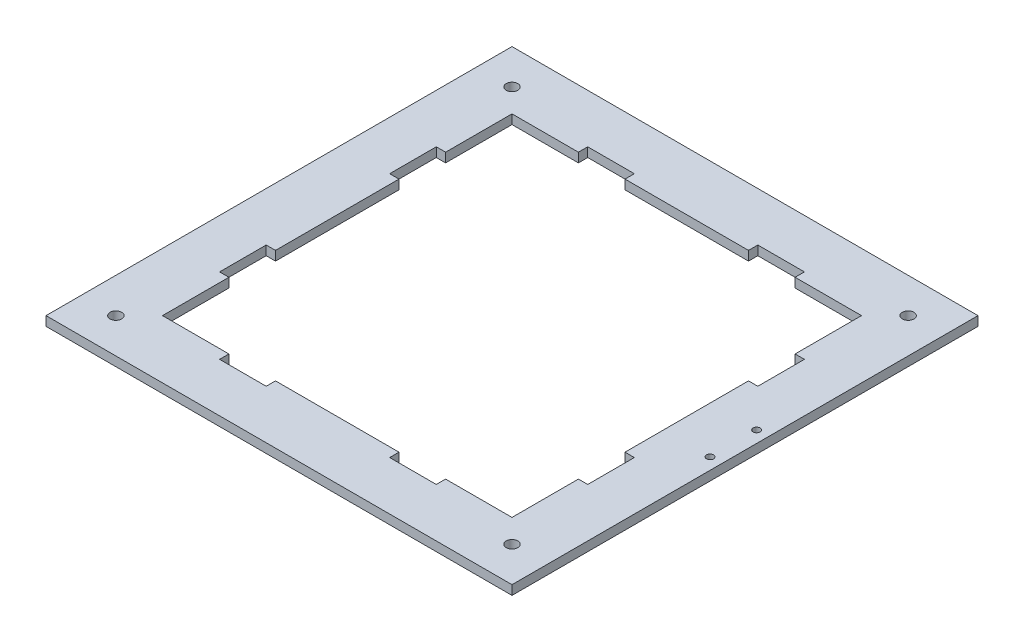
SolidWorks part; units mm, degrees
ref_plane "Alzado" through (0, 0, 0) normal (0, 0, 1) x (1, 0, 0)
ref_plane "Planta" through (0, 0, 0) normal (0, 1, 0) x (1, 0, 0)
ref_plane "Vista lateral" through (0, 0, 0) normal (1, 0, 0) x (0, 0, -1)
sketch "Croquis1" plane through (0, 0, 0) normal (0, 1, 0) x (1, 0, 0)
  line L0 (100, 15) -> (100, 0) construction
  line L1 (0, 0) -> (200, 0)
  line L2 (0, 0) -> (0, 200)
  line L3 (0, 200) -> (200, 200)
  line L4 (200, 0) -> (200, 200)
  line L5 (15, 15) -> (185, 15) construction
  line L6 (15, 15) -> (15, 185) construction
  line L7 (15, 185) -> (185, 185) construction
  line L8 (185, 15) -> (185, 185) construction
  line L9 (185, 100) -> (200, 100) construction
  circle A0 centre (15, 185) radius 2.5
  circle A1 centre (185, 185) radius 2.5
  circle A2 centre (185, 15) radius 2.5
  circle A3 centre (15, 15) radius 2.5
  dimension "D3" = 5
  dimension "D1" = 200
  dimension "D2" = 170
extrude "Saliente-Extruir1" add sketch "Croquis1" along normal blind 4
sketch "Croquis2" plane through (0, 4, 0) normal (0, 1, 0) x (1, 0, 0)
  line L0 (25, 100) -> (0, 100) construction
  line L1 (25, 25) -> (175, 25)
  line L2 (25, 25) -> (25, 175)
  line L3 (25, 175) -> (175, 175)
  line L4 (175, 25) -> (175, 175)
  line L5 (0, 200) -> (0, 0) construction
  line L6 (100, 25) -> (100, 0) construction
  line L7 (0, 0) -> (200, 0) construction
  line L8 (25, 100) -> (175, 100) construction
  line L9 (100, 175) -> (100, 25) construction
  line L10 (23, 126.5) -> (23, 100) construction
  line L19 (25, 25) -> (175, 25) construction
  line L20 (25, 25) -> (25, 175) construction
  line L21 (25, 175) -> (175, 175) construction
  line L22 (175, 25) -> (175, 175) construction
  line L23 (25, 126.5) -> (21, 126.5)
  line L24 (25, 126.5) -> (25, 146.5)
  line L25 (25, 146.5) -> (21, 146.5)
  line L26 (21, 126.5) -> (21, 146.5)
  line L27 (59.9079, 100) -> (59.9079, 175) construction
  line L28 (25, 136.5) -> (59.9079, 136.5) construction
  line L29 (25, 150.0904) -> (100, 150.0904) construction
  line L30 (63.5, 175) -> (63.5, 150.0904) construction
  line L31 (53.5, 175) -> (73.5, 175)
  line L32 (53.5, 175) -> (53.5, 179)
  line L33 (53.5, 179) -> (73.5, 179)
  line L34 (73.5, 175) -> (73.5, 179)
  line L35 (175, 146.5) -> (179, 146.5)
  line L36 (175, 146.5) -> (175, 126.5)
  line L37 (175, 126.5) -> (179, 126.5)
  line L38 (179, 146.5) -> (179, 126.5)
  line L39 (126.5, 175) -> (146.5, 175)
  line L40 (126.5, 175) -> (126.5, 179)
  line L41 (126.5, 179) -> (146.5, 179)
  line L42 (146.5, 175) -> (146.5, 179)
  line L43 (146.5, 25) -> (146.5, 21)
  line L44 (146.5, 25) -> (126.5, 25)
  line L45 (126.5, 25) -> (126.5, 21)
  line L46 (146.5, 21) -> (126.5, 21)
  line L47 (175, 73.5) -> (175, 53.5)
  line L48 (175, 73.5) -> (179, 73.5)
  line L49 (179, 73.5) -> (179, 53.5)
  line L50 (175, 53.5) -> (179, 53.5)
  line L51 (25, 53.5) -> (21, 53.5)
  line L52 (25, 53.5) -> (25, 73.5)
  line L53 (25, 73.5) -> (21, 73.5)
  line L54 (21, 53.5) -> (21, 73.5)
  line L55 (73.5, 25) -> (53.5, 25)
  line L56 (73.5, 25) -> (73.5, 21)
  line L57 (73.5, 21) -> (53.5, 21)
  line L58 (53.5, 25) -> (53.5, 21)
  line L59 (63.5, 162.5452) -> (100, 162.5452) construction
  line L60 (42.454, 136.5) -> (42.454, 100) construction
  point P18 (25, 100)
  point P19 (100, 175)
  dimension "D1" = 150
  dimension "D2" = 150
  dimension "D3" = 4
  dimension "D4" = 4
  dimension "D5" = 20
  dimension "D6" = 36.5
extrude "Cortar-Extruir1" cut sketch "Croquis2" against normal blind 4 contours L32 L31 L34 L33 | L2 L1 L4 L3 | L43 L46 L45 L44 | L55 L58 L57 L56 | L47 L50 L49 L48 | L35 L38 L37 L36 | L51 L54 L53 L52 | L39 L42 L41 L40 | L24 L23 L26 L25
sketch "Croquis3" plane through (0, 4, 0) normal (0, 1, 0) x (1, 0, 0)
  line L0 (175, 100) -> (200, 100) construction
  line L1 (175, 73.5) -> (175, 126.5) construction
  line L2 (200, 0) -> (200, 200) construction
  line L3 (195, 90) -> (195, 110) construction
  circle A0 centre (195, 110) radius 1.5
  circle A1 centre (195, 90) radius 1.5
  point P9 (195, 100)
  dimension "D2" = 3
  dimension "D1" = 5
  dimension "D3" = 20
extrude "Cortar-Extruir2" cut sketch "Croquis3" against normal blind 10
